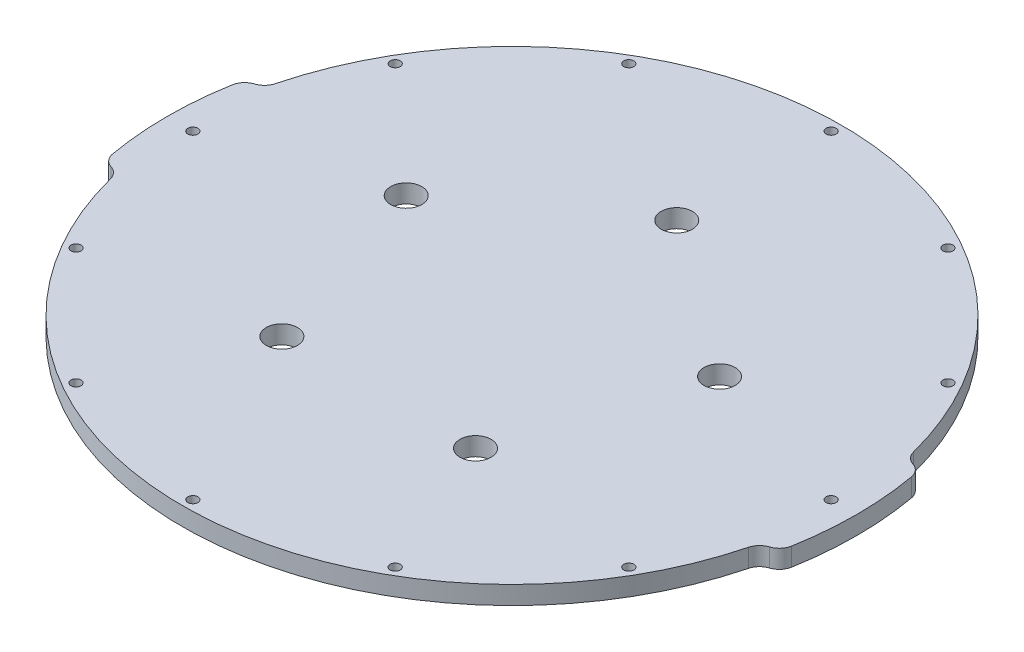
SolidWorks part; units mm, degrees
material "6061 Alloy"
ref_plane "Front Plane" through (0, 0, 0) normal (0, 0, 1) x (1, 0, 0)
ref_plane "Top Plane" through (0, 0, 0) normal (0, 1, 0) x (1, 0, 0)
ref_plane "Right Plane" through (0, 0, 0) normal (1, 0, 0) x (0, 0, -1)
sketch "Sketch1" plane through (0, 0, 0) normal (0, 1, 0) x (1, 0, 0)
  line L0 (0, 0) -> (-111.234, 19.6136) construction
  line L1 (0, 0) -> (-139.7786, 0) construction
  line L2 (0, 0) -> (-111.234, -19.6136) construction
  line L3 (0, 0) -> (111.234, 19.6136) construction
  line L4 (0, 0) -> (111.234, -19.6136) construction
  circle A0 centre (0, 0) radius 104.55 construction
  circle A1 centre (0, 104.55) radius 1.65
  circle A2 centre (52.275, 90.543) radius 1.65
  circle A3 centre (90.543, 52.275) radius 1.65
  circle A4 centre (104.55, 0) radius 1.65
  circle A5 centre (90.543, -52.275) radius 1.65
  circle A6 centre (52.275, -90.543) radius 1.65
  circle A7 centre (0, -104.55) radius 1.65
  circle A8 centre (-52.275, -90.543) radius 1.65
  circle A9 centre (-90.543, -52.275) radius 1.65
  circle A10 centre (-104.55, 0) radius 1.65
  circle A11 centre (-90.543, 52.275) radius 1.65
  circle A12 centre (-52.275, 90.543) radius 1.65
  circle A13 centre (0, 0) radius 107.95 construction
  circle A14 centre (0, 0) radius 112.95 construction
  arc A15 (-111.234, -19.6136) -> (-111.234, 19.6136) centre (0, 0) cw
  arc A16 (111.234, -19.6136) -> (111.234, 19.6136) centre (0, 0) ccw
  arc A17 (-111.234, -19.6136) -> (-105.328, -23.6479) centre (-106.31, -18.7453) ccw
  arc A18 (-111.234, 19.6136) -> (-105.328, 23.6479) centre (-106.31, 18.7453) cw
  arc A19 (111.234, -19.6136) -> (105.328, -23.6479) centre (106.31, -18.7453) cw
  arc A20 (111.234, 19.6136) -> (105.328, 23.6479) centre (106.31, 18.7453) ccw
  arc A21 (-105.328, 23.6479) -> (105.328, 23.6479) centre (0, 0) cw
  arc A22 (105.328, -23.6479) -> (-105.328, -23.6479) centre (0, 0) cw
  point P30 (0, 0)
  dimension "D1" = 3.3
  dimension "D2" = 209.1
  dimension "D4" = 215.9
  dimension "D5" = 5
  dimension "D6" = 10
  dimension "D3" = 12
extrude "Boss-Extrude1" add sketch "Sketch1" along normal blind 6
fillet "Fillet1" radius 5 4 edges at (105.328, 3, 23.6479) (105.328, 3, -23.6479) (-105.328, 3, -23.6479) (-105.328, 3, 23.6479)
sketch "Sketch2" plane through (0, 6, 0) normal (0, 1, 0) x (1, 0, 0)
  line L0 (0, 0) -> (0, -107.95) construction
  circle A0 centre (0, 53.975) radius 5.1
  circle A1 centre (0, 0) radius 53.975 construction
  circle A2 centre (51.3333, 16.6792) radius 5.1
  circle A3 centre (31.7257, -43.6667) radius 5.1
  circle A4 centre (-31.7257, -43.6667) radius 5.1
  circle A5 centre (-51.3333, 16.6792) radius 5.1
  arc A6 (-104.514, -27.019) -> (104.514, -27.019) centre (0, 0) ccw construction
  point P5 (0, -53.975)
  point P16 (0, 0)
  dimension "D1" = 10.2
  dimension "D2" = 5
extrude "Cut-Extrude1" cut sketch "Sketch2" against normal through all
